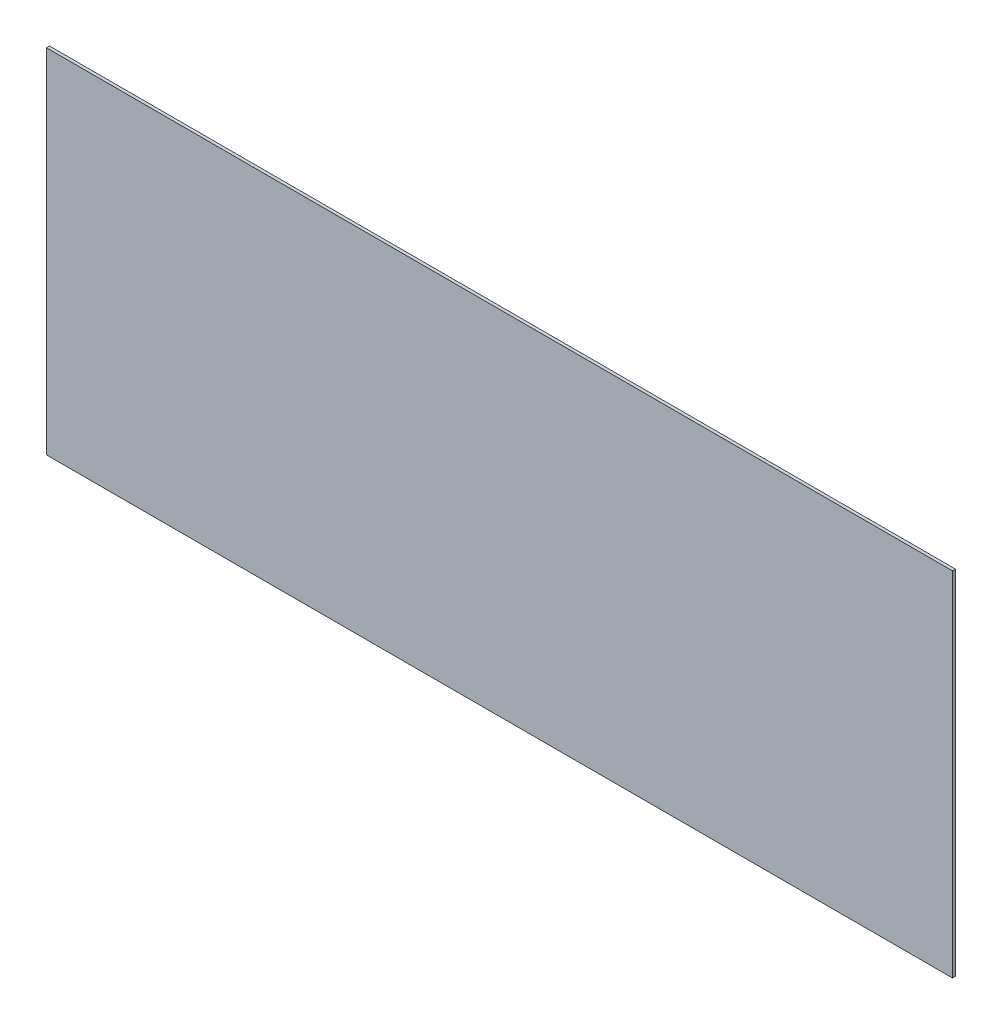
SolidWorks part; units mm, degrees
ref_plane "Front Plane" through (0, 0, 0) normal (0, 0, 1) x (1, 0, 0)
ref_plane "Top Plane" through (0, 0, 0) normal (0, 1, 0) x (1, 0, 0)
ref_plane "Right Plane" through (0, 0, 0) normal (1, 0, 0) x (0, 0, -1)
sketch "Sketch2" plane through (0, 0, 0) normal (0, 0, 1) x (1, 0, 0)
  line L1 (-474.765, 184.765) -> (474.765, 184.765)
  line L2 (-474.765, 184.765) -> (-474.765, -184.765)
  line L3 (-474.765, -184.765) -> (474.765, -184.765)
  line L4 (474.765, 184.765) -> (474.765, -184.765)
  line L5 (-474.765, 184.765) -> (474.765, -184.765) construction
  line L6 (-474.765, -184.765) -> (474.765, 184.765) construction
  point P0 (0, 0)
  dimension "Length 1" = 949.53
  dimension "Length 2" = 369.53
extrude "Boss-Extrude1" add sketch "Sketch2" along normal blind 3.175
